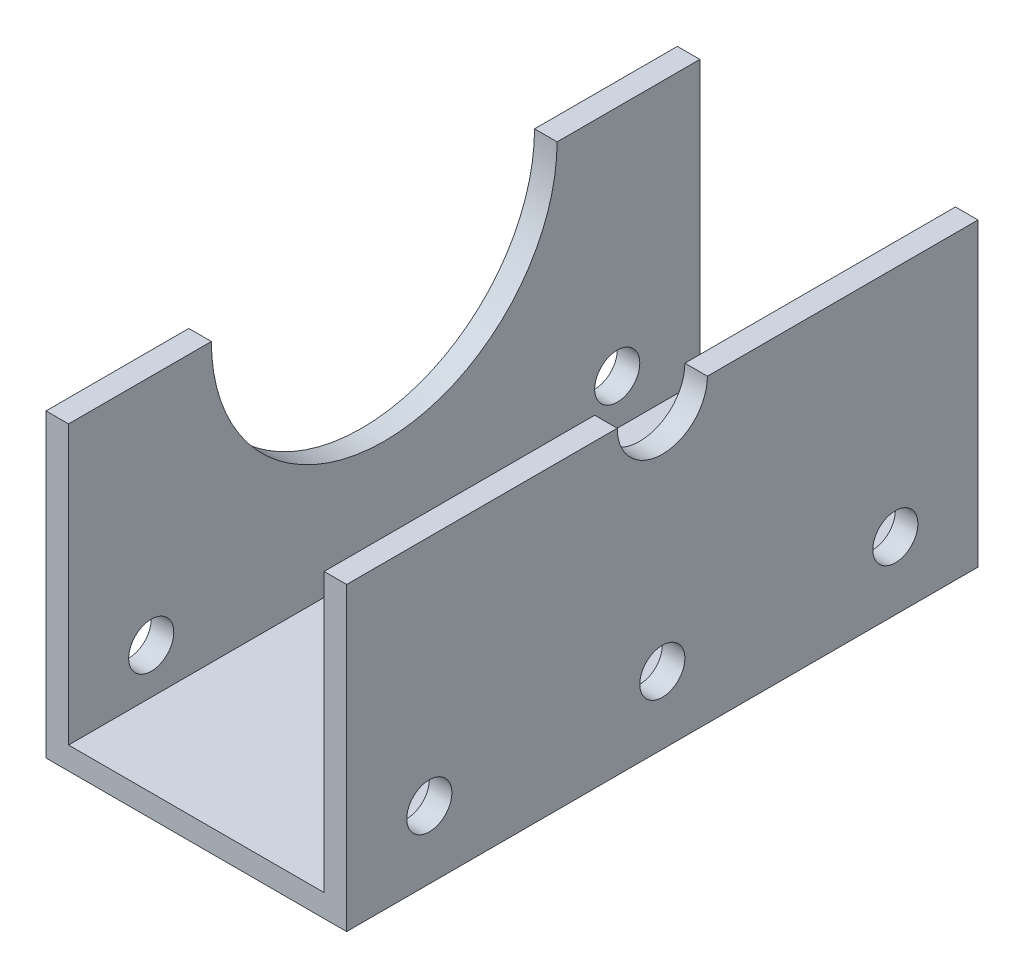
SolidWorks part; units mm, degrees
ref_plane "Plan de face" through (0, 0, 0) normal (0, 0, 1) x (1, 0, 0)
ref_plane "Plan de dessus" through (0, 0, 0) normal (0, 1, 0) x (1, 0, 0)
ref_plane "Plan de droite" through (0, 0, 0) normal (1, 0, 0) x (0, 0, -1)
sketch "Esquisse1" plane through (0, 0, 0) normal (0, 0, 1) x (1, 0, 0)
  line L0 (-15.6136, 13.1813) -> (-15.6136, -6.8187)
  line L1 (-15.6136, -6.8187) -> (4.3864, -6.8187)
  line L2 (4.3864, -6.8187) -> (4.3864, 13.1813)
  line L3 (4.3864, 13.1813) -> (2.8864, 13.1813)
  line L4 (2.8864, 13.1813) -> (2.8864, -5.3187)
  line L5 (2.8864, -5.3187) -> (-14.1136, -5.3187)
  line L6 (-14.1136, -5.3187) -> (-14.1136, 13.1813)
  line L7 (-14.1136, 13.1813) -> (-15.6136, 13.1813)
  dimension "D1" = 1.5
  dimension "D2" = 1.5
  dimension "D3" = 1.5
  dimension "D4" = 20
  dimension "D5" = 20
  dimension "D6" = 20
extrude "Extrusion1" add sketch "Esquisse1" along normal blind 42
sketch "Esquisse2" plane through (4.3864, 0, 0) normal (1, 0, 0) x (0, 0, -1)
  line L0 (-36.5, -2.3187) -> (-5.5, -2.3187) construction
  line L3 (-42, -6.8187) -> (0, -6.8187) construction
  line L4 (0, -6.8187) -> (0, 13.1813) construction
  circle A0 centre (-36.5, -2.3187) radius 1.5
  circle A1 centre (-5.5, -2.3187) radius 1.5
  dimension "D2" = 31
  dimension "D1" = 4.5
  dimension "D3" = 5.5
extrude "Extrusion2" cut sketch "Esquisse2" against normal through all
sketch "Esquisse3" plane through (4.3864, 0, 0) normal (1, 0, 0) x (0, 0, -1)
  line L0 (0, -6.8187) -> (0, 13.1813) construction
  line L1 (-42, -6.8187) -> (0, -6.8187) construction
  circle A0 centre (-21, -2.3187) radius 1.5
  dimension "D1" = 21
  dimension "D2" = 4.5
extrude "Extrusion3" cut sketch "Esquisse3" against normal blind 10
sketch "Esquisse4" plane through (-15.6136, 0, 0) normal (-1, 0, 0) x (0, 0, 1)
  line L0 (5.5, -2.3187) -> (36.5, -2.3187) construction
  line L1 (5.5, -2.3187) -> (5.5, 28.6813) construction
  line L2 (36.5, -2.3187) -> (36.5, 28.6813) construction
  line L3 (5.5, 28.6813) -> (36.5, 28.6813) construction
  line L4 (21, 28.6813) -> (21, -2.3187) construction
  line L5 (5.5, 13.1813) -> (36.5, 13.1813) construction
  circle A0 centre (21, 13.1813) radius 11.5
  dimension "D1" = 31
extrude "Extrusion4" cut sketch "Esquisse4" against normal blind 10
sketch "Esquisse5" plane through (4.3864, 0, 0) normal (1, 0, 0) x (0, 0, -1)
  line L0 (-36.5, -2.3187) -> (-5.5, -2.3187) construction
  line L1 (-36.5, -2.3187) -> (-36.5, 28.6813) construction
  line L2 (-5.5, -2.3187) -> (-5.5, 28.6813) construction
  line L3 (-36.5, 28.6813) -> (-5.5, 28.6813) construction
  line L4 (-21, 28.6813) -> (-21, -2.3187) construction
  line L5 (-36.5, 13.1813) -> (-5.5, 13.1813) construction
  circle A0 centre (-21, 13.1813) radius 3
  dimension "D1" = 31
extrude "Extrusion5" cut sketch "Esquisse5" against normal blind 10
